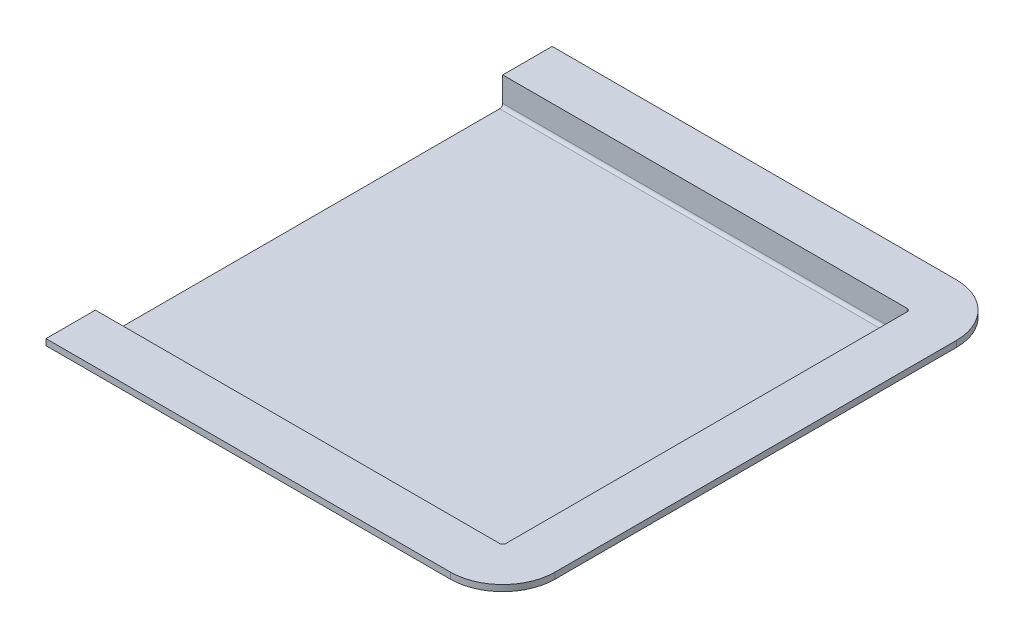
SolidWorks part; units mm, degrees
ref_plane "Front Plane" through (0, 0, 0) normal (0, 0, 1) x (1, 0, 0)
ref_plane "Top Plane" through (0, 0, 0) normal (0, 1, 0) x (1, 0, 0)
ref_plane "Right Plane" through (0, 0, 0) normal (1, 0, 0) x (0, 0, -1)
sketch "Sketch1" plane through (0, 0, 0) normal (0, 1, 0) x (1, 0, 0)
  line L0 (-66, 0) -> (66, 0) construction
  line L1 (-66, 66) -> (66, 66)
  line L2 (-66, 66) -> (-66, -66)
  line L3 (-66, -66) -> (66, -66)
  line L4 (66, 66) -> (66, -66)
  point P6 (0, 0)
  dimension "D1" = 132
  dimension "D2" = 132
extrude "Boss-Extrude1" add sketch "Sketch1" along normal blind 9
shell "Shell1" thickness 2
sketch "Sketch2" plane through (-68, 0, 0) normal (-1, 0, 0) x (0, 0, 1)
  line L1 (-87.8508, -19.4743) -> (87.8508, -19.4743)
  line L2 (-87.8508, -19.4743) -> (-87.8508, 19.4743)
  line L3 (-87.8508, 19.4743) -> (87.8508, 19.4743)
  line L4 (87.8508, -19.4743) -> (87.8508, 19.4743)
  line L5 (-87.8508, -19.4743) -> (87.8508, 19.4743) construction
  line L6 (-87.8508, 19.4743) -> (87.8508, -19.4743) construction
  point P0 (0, 0)
extrude "Cut-Extrude1" cut sketch "Sketch2" against normal up to surface (2 mm away) up to face at (-66, 4.5, 0)
fillet "Fillet1" radius 1 5 edges at (0, 0, 66) (66, 0, 0) (0, 0, -66) (66, 4.5, 66) (66, 4.5, -66)
fillet "Fillet2" radius 3 5 edges at (68, 3.5, 68) (68, 3.5, -68) (1, -2, -68) (68, -2, 0) (1, -2, 68)
sketch "Sketch4" plane through (0, 9, 0) normal (0, 1, 0) x (1, 0, 0)
  line L3 (-66, 82) -> (-66, 68)
  line L4 (-66, -82) -> (-66, -68)
  line L5 (-66, -68) -> (65, -68) construction
  line L6 (-66, -82) -> (65, -82)
  line L7 (82, -65) -> (82, 65)
  line L8 (65, 82) -> (-66, 82)
  line L9 (-66, -82) -> (65, -82)
  line L10 (82, -65) -> (82, 65)
  line L11 (65, 82) -> (-66, 82)
  line L12 (68, -65) -> (68, 65) construction
  line L13 (65, 68) -> (-66, 68) construction
  line L14 (-66, -68) -> (65, -68)
  line L15 (68, -65) -> (68, 65)
  line L16 (65, 68) -> (-66, 68)
  arc A2 (65, -68) -> (68, -65) centre (65, -65) ccw construction
  arc A3 (68, 65) -> (65, 68) centre (65, 65) ccw construction
  arc A4 (65, -82) -> (82, -65) centre (65, -65) ccw
  arc A5 (82, 65) -> (65, 82) centre (65, 65) ccw
  arc A6 (65, -82) -> (82, -65) centre (65, -65) ccw
  arc A7 (82, 65) -> (65, 82) centre (65, 65) ccw
  arc A8 (65, -68) -> (68, -65) centre (65, -65) ccw
  arc A9 (68, 65) -> (65, 68) centre (65, 65) ccw
  dimension "D1" = 14
extrude "Boss-Extrude2" add sketch "Sketch4" against normal blind 2
fillet "Fillet3" radius 3 5 edges at (-0.5, 7, 68) (67.1213, 7, 67.1213) (68, 7, 0) (67.1213, 7, -67.1213) (-0.5, 7, -68)
